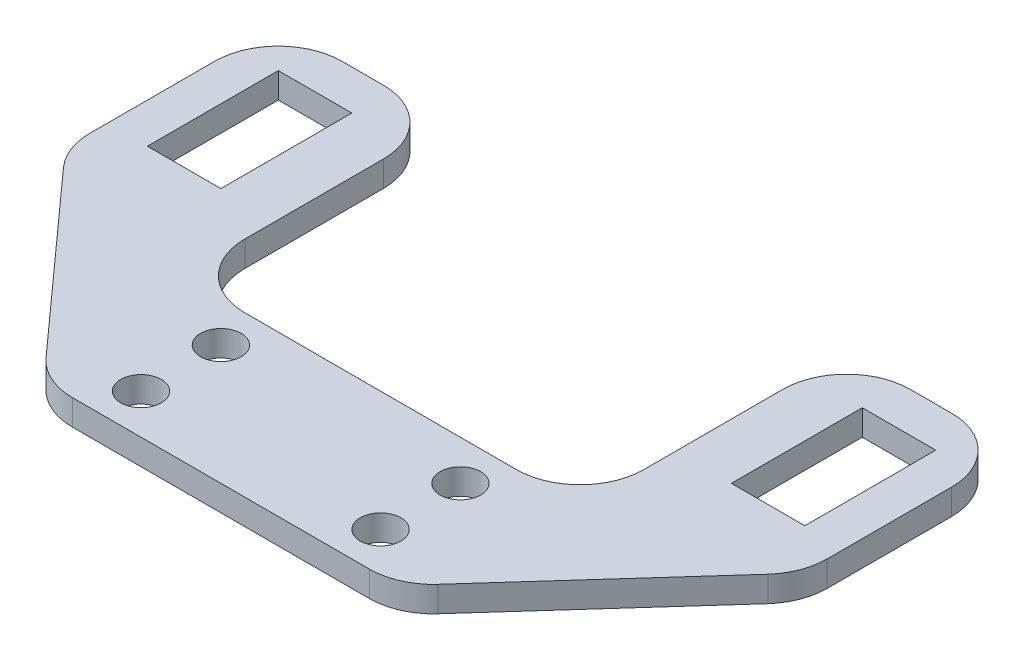
SolidWorks part; units mm, degrees
ref_plane "Front" through (0, 0, 0) normal (0, 0, 1) x (1, 0, 0)
ref_plane "Top" through (0, 0, 0) normal (0, 1, 0) x (1, 0, 0)
ref_plane "Right" through (0, 0, 0) normal (1, 0, 0) x (0, 0, -1)
sketch "Sketch1" plane through (0, 0, 0) normal (0, 1, 0) x (1, 0, 0)
  line L0 (29.3183, 33.8903) -> (29.3183, 0) construction
  line L1 (0, 0) -> (58.6366, 0)
  line L2 (0, 0) -> (0, 33.8903)
  line L3 (0, 33.8903) -> (58.6366, 33.8903)
  line L4 (58.6366, 0) -> (58.6366, 33.8903)
  line L5 (3.175, 30.7153) -> (9.017, 30.7153)
  line L6 (3.175, 30.7153) -> (3.175, 20.3013)
  line L7 (3.175, 20.3013) -> (9.017, 20.3013)
  line L8 (9.017, 30.7153) -> (9.017, 20.3013)
  line L9 (9.017, 20.3013) -> (19.7933, 9.525) construction
  line L10 (55.4616, 20.3013) -> (49.6196, 20.3013)
  line L11 (49.6196, 30.7153) -> (49.6196, 20.3013)
  line L12 (55.4616, 30.7153) -> (49.6196, 30.7153)
  line L13 (55.4616, 30.7153) -> (55.4616, 20.3013)
  circle A0 centre (19.7933, 9.525) radius 1.6129
  circle A1 centre (19.7933, 3.175) radius 1.6129
  circle A2 centre (38.8433, 3.175) radius 1.6129
  circle A3 centre (38.8433, 9.525) radius 1.6129
  dimension "D5" = 3.2258
  dimension "D1" = 10.414
  dimension "D2" = 5.842
  dimension "D3" = 6.35
  dimension "D4" = 9.525
  dimension "D6" = 15.24
  dimension "D7" = 45
  dimension "D8" = 3.175
  dimension "D9" = 3.175
  dimension "D10" = 3.175
extrude "Boss-Extrude1" add sketch "Sketch1" along normal blind 2.032
sketch "Sketch2" plane through (0, 2.032, 0) normal (0, 1, 0) x (1, 0, 0)
  line L0 (13.4433, 33.8903) -> (13.4433, 12.7)
  line L1 (58.6366, 33.8903) -> (0, 33.8903) construction
  line L2 (13.4433, 12.7) -> (45.1933, 12.7)
  line L3 (45.1933, 12.7) -> (45.1933, 33.8903)
  line L4 (45.1933, 33.8903) -> (13.4433, 33.8903)
  line L5 (0, 0) -> (58.6366, 0) construction
  line L6 (0, 16.9452) -> (15.24, 0)
  line L7 (0, 33.8903) -> (0, 0) construction
  line L8 (15.24, 0) -> (0, 0)
  line L9 (0, 0) -> (0, 16.9452)
  line L10 (29.3183, 33.8903) -> (29.3183, 0) construction
  line L11 (43.3966, 0) -> (58.6366, 0)
  line L12 (58.6366, 16.9452) -> (43.3966, 0)
  line L13 (58.6366, 0) -> (58.6366, 16.9452)
  point P8 (29.3183, 0)
  point P9 (29.3183, 12.7)
  point P10 (29.3183, 33.8903)
  dimension "D1" = 12.7
  dimension "D2" = 31.75
  dimension "D3" = 15.24
extrude "Cut-Extrude1" cut sketch "Sketch2" against normal through all
fillet "Fillet1" radius 5.08 10 edges at (43.3966, 1.016, 0) (15.24, 1.016, 0) (0, 1.016, -16.9452) (58.6366, 1.016, -16.9452) (0, 1.016, -33.8903) (58.6366, 1.016, -33.8903) (13.4433, 1.016, -33.8903) (45.1933, 1.016, -33.8903) (45.1933, 1.016, -12.7) (13.4433, 1.016, -12.7)
